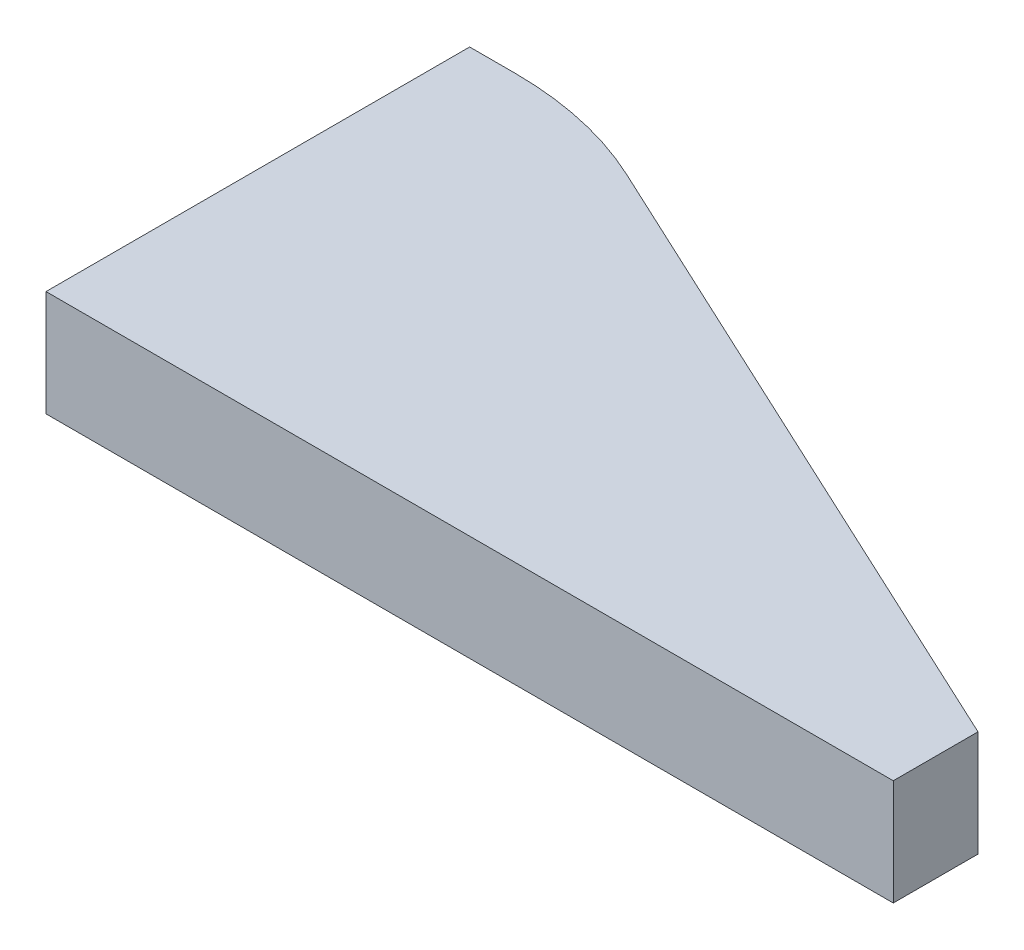
SolidWorks part; units mm, degrees
ref_plane "Front Plane" through (0, 0, 0) normal (0, 0, 1) x (1, 0, 0)
ref_plane "Top Plane" through (0, 0, 0) normal (0, 1, 0) x (1, 0, 0)
ref_plane "Right Plane" through (0, 0, 0) normal (1, 0, 0) x (0, 0, -1)
sketch "Sketch1" plane through (0, 0, 0) normal (0, 1, 0) x (1, 0, 0)
  line L1 (0, 0) -> (25.4, 0)
  line L2 (0, 0) -> (0, 12.7)
  line L3 (0, 12.7) -> (25.4, 12.7)
  line L4 (25.4, 0) -> (25.4, 12.7)
  dimension "D1" = 25.4
  dimension "D2" = 12.7
extrude "Boss-Extrude1" add sketch "Sketch1" along normal blind 3.175
chamfer "Chamfer1" distance 10.16 angle 65 1 edges at (25.4, 1.5875, -12.7)
fillet "Fillet1" radius 10.16 1 edges at (3.6118, 1.5875, -12.7)
